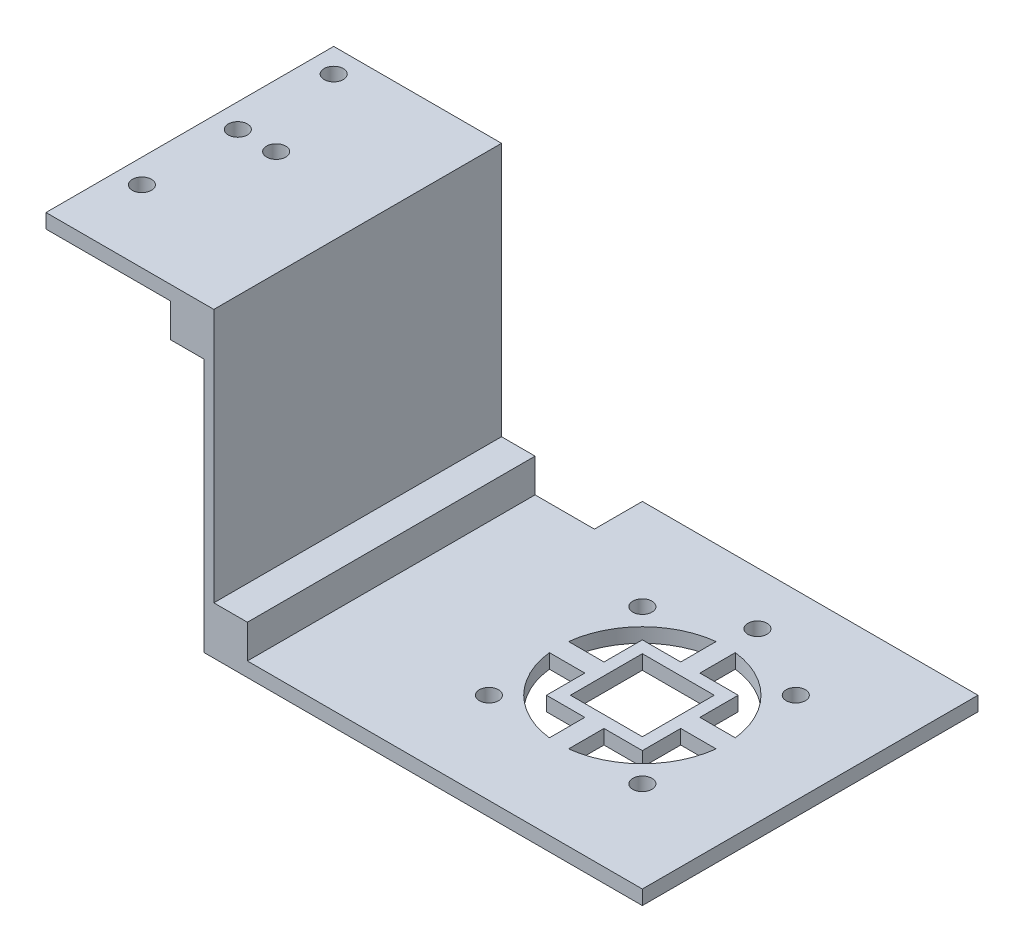
SolidWorks part; units mm, degrees
ref_plane "Ön Düzlem" through (0, 0, 0) normal (0, 0, 1) x (1, 0, 0)
ref_plane "Üst Düzlem" through (0, 0, 0) normal (0, 1, 0) x (1, 0, 0)
ref_plane "Sağ Düzlem" through (0, 0, 0) normal (1, 0, 0) x (0, 0, -1)
sketch "Çizim1" plane through (0, 0, 0) normal (0, 1, 0) x (1, 0, 0)
  line L1 (-37.5, 25) -> (37.5, 25)
  line L2 (-37.5, 25) -> (-37.5, -25)
  line L3 (-37.5, -25) -> (37.5, -25)
  line L4 (37.5, 25) -> (37.5, -25)
  line L5 (-37.5, 25) -> (37.5, -25) construction
  line L6 (-37.5, -25) -> (37.5, 25) construction
  point P0 (0, 0)
  dimension "D1" = 50
  dimension "D2" = 75
extrude "Yükseklik-Ekstrüzyon1" add sketch "Çizim1" along normal blind 3
sketch "Çizim8" plane through (0, 3, 0) normal (0, 1, 0) x (1, 0, 0)
  line L3 (-37.5, -25) -> (37.5, -25) construction
  line L4 (-37.5, 25) -> (-17.868, 25)
  line L5 (-37.5, 25) -> (-37.5, -25)
  line L6 (-37.5, -25) -> (-17.868, -25)
  line L7 (-17.868, 25) -> (-17.868, -25)
  line L8 (-37.5, 25) -> (-17.868, -25) construction
  line L9 (-37.5, -25) -> (-17.868, 25) construction
  point P4 (-27.684, 0)
extrude "Kes-Ekstrüzyon4" cut sketch "Çizim8" against normal blind 3
sketch "Çizim9" plane through (0, 0, 0) normal (0, 1, 0) x (1, 0, 0)
  line L0 (-17.868, 25) -> (-19.868, 25)
  line L1 (-19.868, 25) -> (-19.868, -25)
  line L2 (-19.868, -25) -> (-17.868, -25)
  line L3 (-17.868, -25) -> (-17.868, 25)
extrude "Yükseklik-Ekstrüzyon2" add sketch "Çizim9" along normal blind 60
sketch "Çizim10" plane through (0, 60, 0) normal (0, 1, 0) x (1, 0, 0)
  line L0 (-17.868, 25) -> (-52.868, 25)
  line L1 (-52.868, 25) -> (-52.868, -25)
  line L2 (-52.868, -25) -> (-17.868, -25)
  line L3 (-17.868, -25) -> (-17.868, 25)
  dimension "D1" = 35
extrude "Yükseklik-Ekstrüzyon3" add sketch "Çizim10" along normal blind 3
sketch "Çizim12" plane through (0, 63, 0) normal (0, 1, 0) x (1, 0, 0)
  circle A0 centre (-39.868, 0) radius 2
  circle A1 centre (-47.868, 0) radius 2
  circle A2 centre (-47.868, 20) radius 2
  circle A3 centre (-47.868, -20) radius 2
extrude "Kes-Ekstrüzyon5" cut sketch "Çizim12" against normal blind 3
sketch "Çizim13" plane through (0, 3, 0) normal (0, 1, 0) x (1, 0, 0)
  line L0 (37.5, 25) -> (57.5, 25)
  line L1 (57.5, 25) -> (57.5, -25)
  line L2 (57.5, -25) -> (37.5, -25)
  line L3 (37.5, -25) -> (37.5, 25)
extrude "Yükseklik-Ekstrüzyon4" add sketch "Çizim13" against normal blind 3
sketch "Çizim14" plane through (0, 3, 0) normal (0, 1, 0) x (1, 0, 0)
  circle A0 centre (20.5, 16) radius 2
  circle A1 centre (52.5, 16) radius 2
  circle A2 centre (20.5, -16) radius 2
  circle A3 centre (52.5, -16) radius 2
extrude "Kes-Ekstrüzyon6" cut sketch "Çizim14" against normal blind 3
sketch "Çizim15" plane through (0, 3, 0) normal (0, 1, 0) x (1, 0, 0)
  line L2 (29, 7.5) -> (44, 7.5)
  line L3 (29, 7.5) -> (29, -7.5)
  line L4 (29, -7.5) -> (44, -7.5)
  line L5 (44, 7.5) -> (44, -7.5)
  line L6 (29, 7.5) -> (44, -7.5) construction
  line L7 (29, -7.5) -> (44, 7.5) construction
  point P4 (36.5, 0)
extrude "Kes-Ekstrüzyon7" cut sketch "Çizim15" against normal blind 3
sketch "Çizim16" plane through (0, 3, 0) normal (0, 1, 0) x (1, 0, 0)
  line L0 (46.5, 2) -> (53.8853, 2)
  line L1 (26.5, 10) -> (34.5, 10)
  line L2 (26.5, 10) -> (26.5, 2)
  line L3 (26.5, -10) -> (34.5, -10)
  line L4 (46.5, 10) -> (46.5, 2)
  line L7 (34.5, 10) -> (34.5, 17.3853)
  line L8 (46.5, -2) -> (53.8853, -2)
  line L9 (38.5, 10) -> (38.5, 17.3853)
  line L10 (38.5, 10) -> (46.5, 10)
  line L11 (38.5, -10) -> (38.5, -17.3853)
  line L12 (34.5, -10) -> (34.5, -17.3853)
  line L13 (26.5, -2) -> (19.1147, -2)
  line L14 (26.5, 2) -> (19.1147, 2)
  line L15 (26.5, -2) -> (26.5, -10)
  line L16 (38.5, -10) -> (46.5, -10)
  line L17 (46.5, -2) -> (46.5, -10)
  arc A0 (34.5, 17.3853) -> (19.1147, 2) centre (36.5, 0) ccw
  arc A2 (19.1147, -2) -> (34.5, -17.3853) centre (36.5, 0) ccw
  arc A3 (38.5, -17.3853) -> (53.8853, -2) centre (36.5, 0) ccw
  arc A4 (53.8853, 2) -> (38.5, 17.3853) centre (36.5, 0) ccw
  dimension "D1" = 4
extrude "Kes-Ekstrüzyon8" cut sketch "Çizim16" against normal blind 3
sketch "Çizim17" plane through (0, 3, 0) normal (0, 1, 0) x (1, 0, 0)
  line L0 (57.5, 25) -> (62.5, 25)
  line L1 (62.5, 25) -> (62.5, -25)
  line L2 (62.5, -25) -> (57.5, -25)
  line L3 (57.5, -25) -> (57.5, 25)
extrude "Yükseklik-Ekstrüzyon5" add sketch "Çizim17" against normal blind 3
sketch "Çizim18" plane through (0, 3, 0) normal (0, 1, 0) x (1, 0, 0)
  line L0 (1.5, 25) -> (62.5, 25)
  line L1 (1.5, -35) -> (71.5, -35)
  line L2 (1.5, -35) -> (1.5, -25)
  line L3 (1.5, 35) -> (71.5, 35)
  line L4 (71.5, -35) -> (71.5, 35)
  line L5 (1.5, -35) -> (71.5, 35) construction
  line L6 (1.5, 35) -> (71.5, -35) construction
  line L7 (62.5, 25) -> (-17.868, 25) construction
  line L8 (62.5, 25) -> (62.5, -25)
  line L9 (62.5, -25) -> (1.5, -25)
  line L10 (-17.868, -25) -> (62.5, -25) construction
  line L11 (1.5, 25) -> (1.5, 35)
  point P0 (36.5, 0)
extrude "Yükseklik-Ekstrüzyon6" add sketch "Çizim18" against normal blind 3
sketch "Çizim19" plane through (0, 3, 0) normal (0, 1, 0) x (1, 0, 0)
  circle A1 centre (36.5, 24) radius 2
extrude "Kes-Ekstrüzyon9" cut sketch "Çizim19" against normal blind 3
sketch "Çizim20" plane through (0, 0, 25) normal (0, 0, 1) x (1, 0, 0)
  line L0 (-19.868, 60) -> (-26.868, 60)
  line L1 (-52.868, 60) -> (-19.868, 60) construction
  line L2 (-26.868, 60) -> (-26.868, 53)
  line L3 (-26.868, 53) -> (-19.868, 53)
  line L4 (-19.868, 60) -> (-19.868, 0) construction
  line L5 (-19.868, 53) -> (-19.868, 60)
  line L6 (-17.868, 3) -> (-10.868, 3)
  line L7 (-17.868, 3) -> (1.5, 3) construction
  line L8 (-10.868, 3) -> (-10.868, 10)
  line L9 (-10.868, 10) -> (-17.868, 10)
  line L10 (-17.868, 63) -> (-17.868, 3) construction
  line L11 (-17.868, 10) -> (-17.868, 3)
extrude "Yükseklik-Ekstrüzyon7" add sketch "Çizim20" against normal blind 50
sketch "Çizim21" plane through (0, 0, 25) normal (0, 0, 1) x (1, 0, 0)
  line L0 (-52.868, 60) -> (-52.868, 63)
  line L1 (-52.868, 63) -> (-17.868, 63)
  line L2 (-17.868, 63) -> (-17.868, 10)
  line L3 (-17.868, 63) -> (-17.868, 10) construction
  line L4 (-17.868, 10) -> (-10.868, 10)
  line L5 (-10.868, 10) -> (-10.868, 3)
  line L6 (-10.868, 3) -> (1.5, 3)
  line L7 (1.5, 3) -> (1.5, 0)
  line L8 (1.5, 0) -> (-19.868, 0)
  line L9 (-19.868, 0) -> (-19.868, 53)
  line L10 (-19.868, 53) -> (-26.868, 53)
  line L11 (-26.868, 53) -> (-26.868, 60)
  line L12 (-26.868, 60) -> (-52.868, 60)
extrude "Yükseklik-Ekstrüzyon8" add sketch "Çizim21" along normal blind 10
